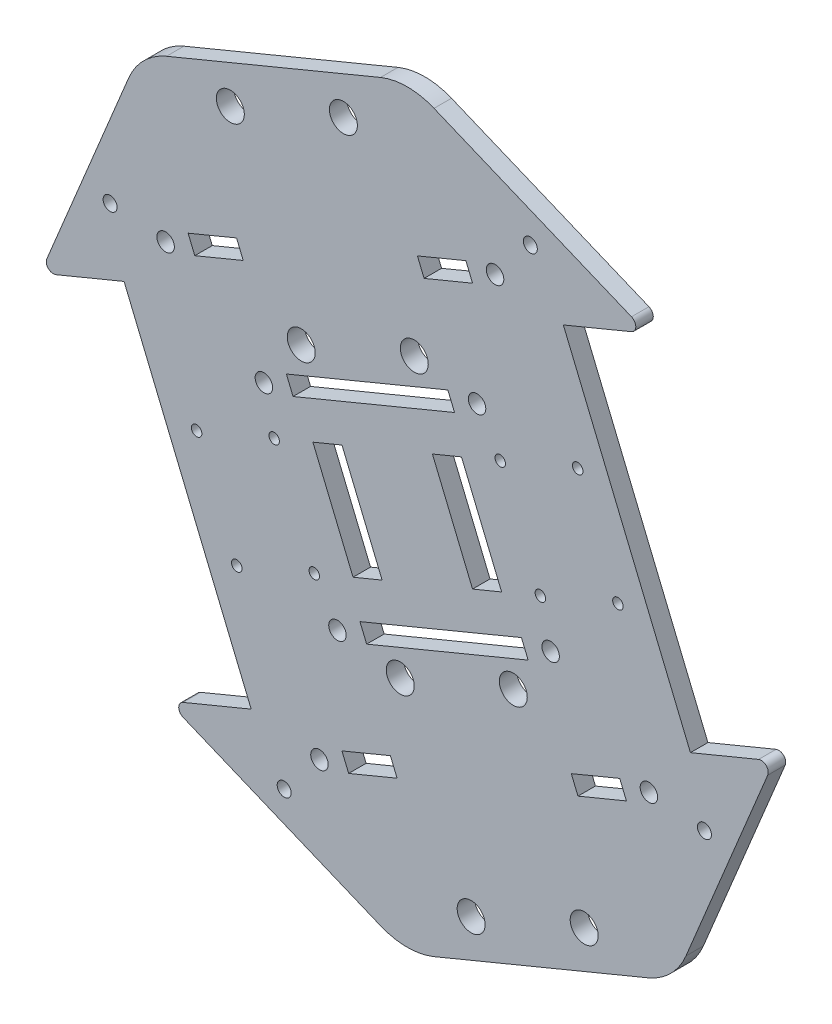
SolidWorks part; units mm, degrees
ref_plane "前视基准面" through (0, 0, 0) normal (0, 0, 1) x (1, 0, 0)
ref_plane "上视基准面" through (0, 0, 0) normal (0, 1, 0) x (1, 0, 0)
ref_plane "右视基准面" through (0, 0, 0) normal (1, 0, 0) x (0, 0, -1)
sketch "草图1" plane through (0, 0, 0) normal (0, 0, 1) x (1, 0, 0)
  line L0 (0, 121.5223) -> (0, -117.9323) construction
  line L1 (-126.6637, 0) -> (129.3981, 0) construction
  line L2 (0, 108.2392) -> (-76.5367, 76.5367)
  line L3 (-76.5367, 76.5367) -> (-108.2392, 0)
  line L4 (-108.2392, 0) -> (-76.5367, -76.5367)
  line L5 (-76.5367, -76.5367) -> (0, -108.2392)
  line L6 (0, -108.2392) -> (76.5367, -76.5367)
  line L7 (76.5367, -76.5367) -> (108.2392, 0)
  line L8 (108.2392, 0) -> (76.5367, 76.5367)
  line L9 (76.5367, 76.5367) -> (0, 108.2392)
  line L14 (-60.2491, -8.7201) -> (-48.7686, -36.4365) construction
  line L15 (-60.2491, -8.7201) -> (-38.076, 0.4643) construction
  line L16 (-48.7686, -36.4365) -> (-26.5955, -27.2521) construction
  line L17 (-38.076, 0.4643) -> (-26.5955, -27.2521) construction
  line L22 (103.4372, 42.8451) -> (-121.0199, -50.1281) construction
  line L23 (-81.0013, 17.8618) -> (-44.6463, -69.9068)
  line L24 (-81.0013, 17.8618) -> (-110.5654, 5.6159)
  line L25 (-44.6463, -69.9068) -> (-74.2105, -82.1526)
  line L26 (-110.5654, 5.6159) -> (-74.2105, -82.1526)
  line L27 (0, 0) -> (65.4267, -157.9539) construction
  line L28 (44.6463, 69.9068) -> (81.0013, -17.8618)
  line L29 (81.0013, -17.8618) -> (110.5654, -5.6159)
  line L30 (74.2105, 82.1526) -> (110.5654, -5.6159)
  line L31 (44.6463, 69.9068) -> (74.2105, 82.1526)
  line L32 (-2.0086, -40.8805) -> (18.2736, -89.8461) construction
  line L33 (-2.0086, -40.8805) -> (30.3272, -27.4866) construction
  line L34 (18.2736, -89.8461) -> (50.6094, -76.4522) construction
  line L35 (30.3272, -27.4866) -> (50.6094, -76.4522) construction
  line L36 (-38.2683, -92.388) -> (38.2683, 92.388) construction
  line L37 (-92.388, 38.2683) -> (92.388, -38.2683) construction
  line L38 (-26.9895, 5.0565) -> (-15.509, -22.6599)
  line L39 (-26.9895, 5.0565) -> (-18.6746, 8.5006)
  line L40 (-15.509, -22.6599) -> (-7.1941, -19.2158)
  line L41 (-18.6746, 8.5006) -> (-7.1941, -19.2158)
  line L42 (7.1941, 19.2158) -> (18.6746, -8.5006)
  line L43 (7.1941, 19.2158) -> (15.509, 22.6599)
  line L44 (18.6746, -8.5006) -> (26.9895, -5.0565)
  line L45 (15.509, 22.6599) -> (26.9895, -5.0565)
  line L50 (-13.5299, -32.6641) -> (-11.6165, -37.2835)
  line L51 (-13.5299, -32.6641) -> (32.6641, -13.5299)
  line L52 (-11.6165, -37.2835) -> (34.5775, -18.1493)
  line L53 (32.6641, -13.5299) -> (34.5775, -18.1493)
  line L54 (-18.6792, -67.2688) -> (-16.7658, -71.8882)
  line L55 (-18.6792, -67.2688) -> (-4.821, -61.5285)
  line L56 (-16.7658, -71.8882) -> (-2.9076, -66.1479)
  line L57 (-4.821, -61.5285) -> (-2.9076, -66.1479)
  line L58 (46.9162, -40.0982) -> (48.8296, -44.7176)
  line L59 (46.9162, -40.0982) -> (60.7744, -34.358)
  line L60 (48.8296, -44.7176) -> (62.6878, -38.9774)
  line L61 (60.7744, -34.358) -> (62.6878, -38.9774)
  line L62 (-60.7744, 34.358) -> (-62.6878, 38.9774)
  line L63 (-60.7744, 34.358) -> (-46.9162, 40.0982)
  line L64 (-46.9162, 40.0982) -> (-48.8296, 44.7176)
  line L65 (-62.6878, 38.9774) -> (-48.8296, 44.7176)
  line L66 (2.9076, 66.1479) -> (16.7658, 71.8882)
  line L67 (4.821, 61.5285) -> (2.9076, 66.1479)
  line L68 (18.6792, 67.2688) -> (16.7658, 71.8882)
  line L69 (4.821, 61.5285) -> (18.6792, 67.2688)
  line L70 (-32.6641, 13.5299) -> (-34.5775, 18.1493)
  line L71 (-34.5775, 18.1493) -> (11.6165, 37.2835)
  line L72 (13.5299, 32.6641) -> (11.6165, 37.2835)
  line L73 (-32.6641, 13.5299) -> (13.5299, 32.6641)
  circle A0 centre (0, 0) radius 100 construction
  circle A5 centre (-60.2491, -8.7201) radius 1.5
  circle A6 centre (-38.076, 0.4643) radius 1.5
  circle A7 centre (-26.5955, -27.2521) radius 1.5
  circle A8 centre (-48.7686, -36.4365) radius 1.5
  circle A9 centre (48.7686, 36.4365) radius 1.5
  circle A10 centre (26.5955, 27.2521) radius 1.5
  circle A11 centre (38.076, -0.4643) radius 1.5
  circle A12 centre (60.2491, 8.7201) radius 1.5
  circle A13 centre (-2.0086, -40.8805) radius 4
  circle A14 centre (18.2736, -89.8461) radius 4
  circle A15 centre (50.6094, -76.4522) radius 4
  circle A16 centre (30.3272, -27.4866) radius 4
  circle A17 centre (-84.9969, 35.2069) radius 2
  circle A18 centre (-35.2069, -84.9969) radius 2
  circle A19 centre (84.9969, -35.2069) radius 2
  circle A20 centre (35.2069, 84.9969) radius 2
  circle A21 centre (-25.1136, -72.6399) radius 2.5
  circle A22 centre (69.1222, -33.6062) radius 2.5
  circle A23 centre (-19.9642, -38.0352) radius 2.5
  circle A24 centre (41.0118, -12.7781) radius 2.5
  circle A25 centre (-69.1222, 33.6062) radius 2.5
  circle A26 centre (25.1136, 72.6399) radius 2.5
  circle A27 centre (19.9642, 38.0352) radius 2.5
  circle A28 centre (-41.0118, 12.7781) radius 2.5
  circle A29 centre (-50.6094, 76.4522) radius 4
  circle A30 centre (-18.2736, 89.8461) radius 4
  circle A31 centre (2.0086, 40.8805) radius 4
  circle A32 centre (-30.3272, 27.4866) radius 4
  dimension "D6" = 9
  dimension "D7" = 15
  dimension "D8" = 35
  dimension "D9" = 53
  dimension "D12" = 3
  dimension "D13" = 3
  dimension "D14" = 3
  dimension "D15" = 3
  dimension "D18" = 8
  dimension "D19" = 8
  dimension "D20" = 8
  dimension "D21" = 8
  dimension "D22" = 8
  dimension "D26" = 4
  dimension "D27" = 4
  dimension "D28" = 4
  dimension "D29" = 4
  dimension "D47" = 5
  dimension "D48" = 5
  dimension "D52" = 2.5
  dimension "D56" = 5
  dimension "D57" = 5
  dimension "D1" = 200
  dimension "D2" = 32
  dimension "D3" = 95
  dimension "D4" = 0
  dimension "D5" = 47.5
  dimension "D10" = 30
  dimension "D11" = 24
  dimension "D16" = 10
  dimension "D17" = 17.5
  dimension "D23" = 8
  dimension "D24" = 8
  dimension "D25" = 8
  dimension "D30" = 9
  dimension "D31" = 30
  dimension "D32" = 30
  dimension "D33" = 9
  dimension "D34" = 15
  dimension "D35" = 15
  dimension "D36" = 12
  dimension "D37" = 12
  dimension "D38" = 5
  dimension "D39" = 5
  dimension "D40" = 15
  dimension "D41" = 15
  dimension "D42" = 28
  dimension "D43" = 28
  dimension "D44" = 25
  dimension "D45" = 25
  dimension "D46" = 40
  dimension "D49" = 2.5
  dimension "D50" = 8
  dimension "D51" = 8
  dimension "D53" = 5
  dimension "D54" = 50
  dimension "D55" = 25
  dimension "D58" = 8
  dimension "D59" = 8
  dimension "D60" = 2.5
  dimension "D61" = 2.5
extrude "凸台-拉伸1" add sketch "草图1" along normal blind 5 contours L28 L31 L9 L2 L3 L24 L23 L25 L5 L6 L7 L29 A11 A9 A8 A7 A6 A5 A10 A12
fillet "圆角1" radius 2 4 edges at (68.5946, 79.8264, 2.5) (104.9495, -7.9421, 2.5) (-68.5946, -79.8264, 2.5) (-104.9495, 7.9421, 2.5)
fillet "圆角2" radius 20 4 edges at (-76.5367, 76.5367, 2.5) (0, 108.2392, 2.5) (76.5367, -76.5367, 2.5) (0, -108.2392, 2.5)
